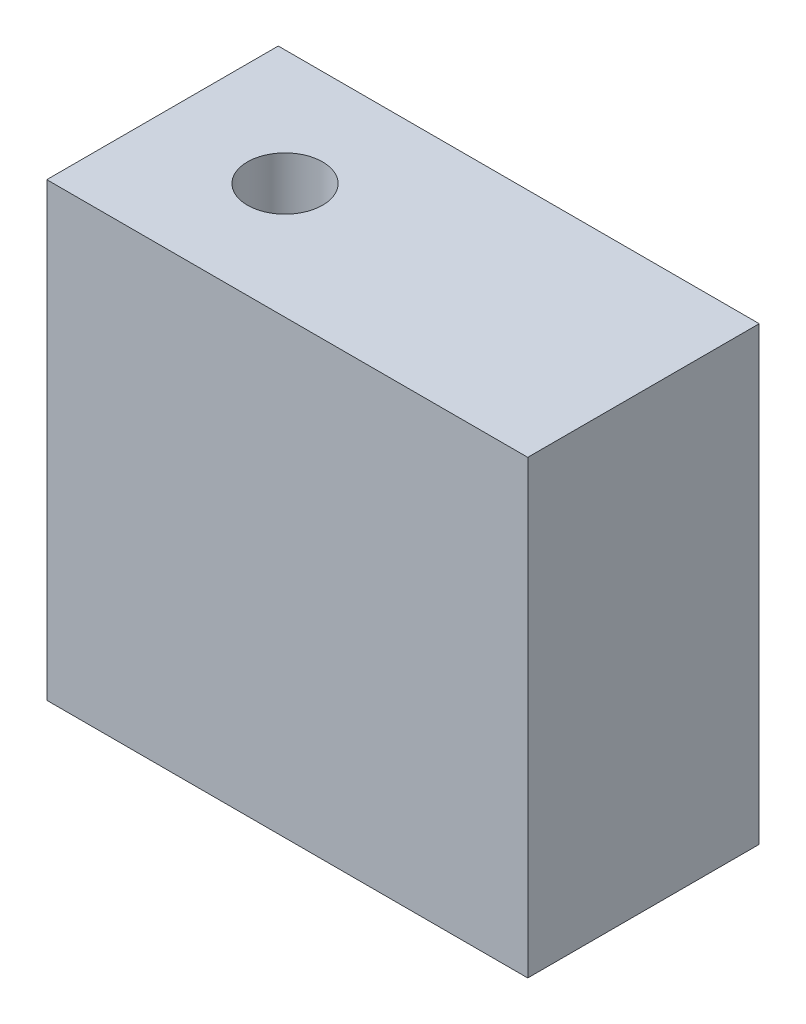
SolidWorks part; units mm, degrees
material "6061-T6 (SS)"
ref_plane "Front Plane" through (0, 0, 0) normal (0, 0, 1) x (1, 0, 0)
ref_plane "Top Plane" through (0, 0, 0) normal (0, 1, 0) x (1, 0, 0)
ref_plane "Right Plane" through (0, 0, 0) normal (1, 0, 0) x (0, 0, -1)
sketch "Sketch1" plane through (0, 0, 0) normal (0, 1, 0) x (1, 0, 0)
  line L1 (0, 0) -> (-40.64, 0)
  line L2 (0, 0) -> (0, -19.558)
  line L3 (0, -19.558) -> (-40.64, -19.558)
  line L4 (-40.64, 0) -> (-40.64, -19.558)
  dimension "D1" = 40.64
  dimension "D2" = 19.558
extrude "Boss-Extrude1" add sketch "Sketch1" along normal blind 38.1
sketch "Sketch2" plane through (0, 38.1, 0) normal (0, 1, 0) x (1, 0, 0)
  line L0 (-40.64, -19.558) -> (-30.2895, -19.558) construction
  line L1 (-40.64, -19.558) -> (0, -19.558) construction
  line L2 (-30.2895, -19.558) -> (-30.2895, 0) construction
  line L3 (0, 0) -> (-40.64, 0) construction
  circle A0 centre (-30.2895, -9.779) radius 3.175
  dimension "D1" = 6.35
extrude "Cut-Extrude1" cut sketch "Sketch2" against normal blind 12.7
